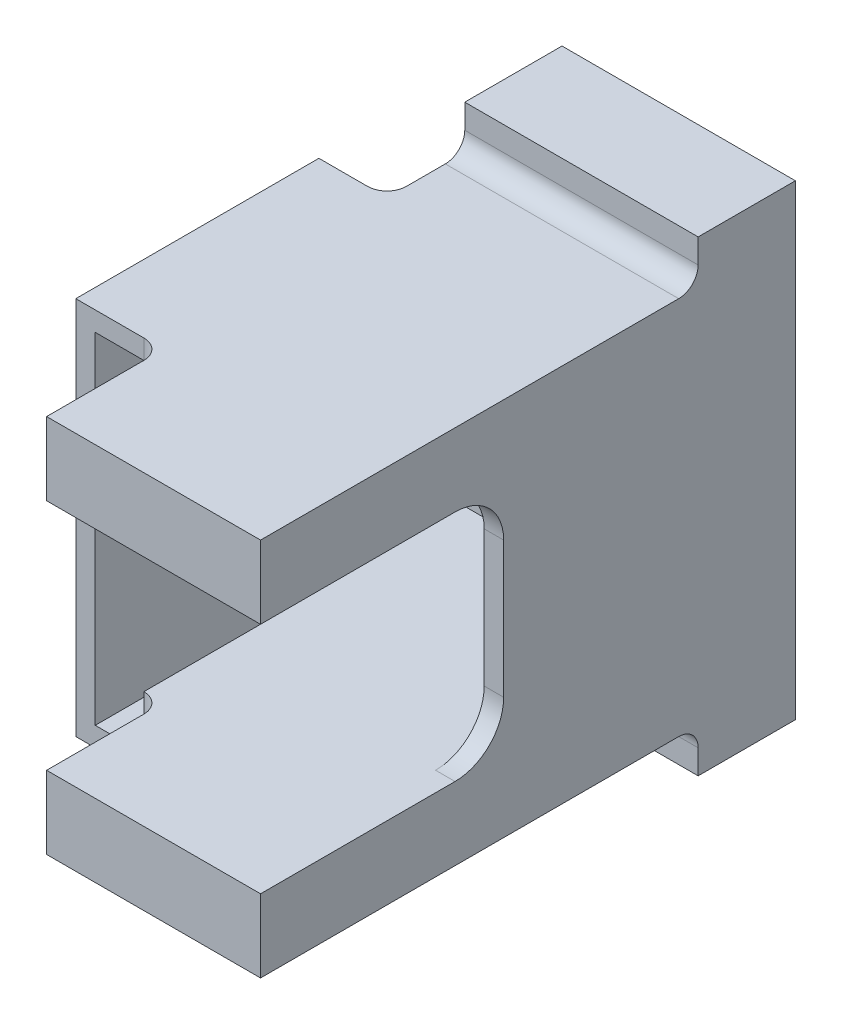
SolidWorks part; units mm, degrees
ref_plane "正面" through (0, 0, 0) normal (0, 0, 1) x (1, 0, 0)
ref_plane "平面" through (0, 0, 0) normal (0, 1, 0) x (1, 0, 0)
ref_plane "右側面" through (0, 0, 0) normal (1, 0, 0) x (0, 0, -1)
sketch "ｽｹｯﾁ2" plane through (0, 0, 0) normal (0, 0, 1) x (1, 0, 0)
  line L1 (-12, 14) -> (12, 14)
  line L2 (-12, 14) -> (-12, -14)
  line L3 (-12, -14) -> (12, -14)
  line L4 (12, 14) -> (12, -14)
  line L5 (-12, 14) -> (12, -14) construction
  line L6 (-12, -14) -> (12, 14) construction
  point P0 (0, 0)
  dimension "D1" = 24
  dimension "D2" = 28
extrude "ﾎﾞｽ - 押し出し1" add sketch "ｽｹｯﾁ2" along normal blind 22
sketch "ｽｹｯﾁ3" plane through (0, 0, 22) normal (0, 0, 1) x (1, 0, 0)
  line L1 (10, 12) -> (-10, 12)
  line L2 (10, 12) -> (10, -12)
  line L3 (10, -12) -> (-10, -12)
  line L4 (-10, 12) -> (-10, -12)
  line L5 (10, 12) -> (-10, -12) construction
  line L6 (10, -12) -> (-10, 12) construction
  point P0 (0, 0)
  dimension "D1" = 24
  dimension "D2" = 20
extrude "ｶｯﾄ - 押し出し1" cut sketch "ｽｹｯﾁ3" against normal blind 18
sketch "ｽｹｯﾁ4" plane through (0, 0, 4) normal (0, 0, 1) x (1, 0, 0)
  line L0 (10, -12) -> (10, 12) construction
  line L1 (-12, 6.5) -> (4, 6.5)
  line L2 (-12, 6.5) -> (-12, -6.5)
  line L3 (-12, -6.5) -> (4, -6.5)
  line L4 (4, 6.5) -> (4, -6.5)
  line L5 (-12, 6.5) -> (4, -6.5) construction
  line L6 (-12, -6.5) -> (4, 6.5) construction
  line L8 (-12, 14) -> (-12, -14) construction
  point P0 (-4, 0)
  dimension "D1" = 6
  dimension "D3" = 13
extrude "ｶｯﾄ - 押し出し3" cut sketch "ｽｹｯﾁ4" against normal through all
sketch "ｽｹｯﾁ6" plane through (-12, 0, 0) normal (-1, 0, 0) x (0, 0, 1)
  line L0 (22, 14) -> (22, -14) construction
  line L1 (22, 12) -> (2, 12)
  line L2 (22, 12) -> (22, -12)
  line L3 (22, -12) -> (2, -12)
  line L4 (2, 12) -> (2, -12)
  line L5 (22, 12) -> (2, -12) construction
  line L6 (22, -12) -> (2, 12) construction
  line L7 (22, 14) -> (0, 14) construction
  line L8 (22, -14) -> (0, -14) construction
  line L9 (0, 14) -> (0, 6.5) construction
  point P0 (12, 0)
  dimension "D1" = 2
  dimension "D2" = 2
  dimension "D3" = 2
extrude "ｶｯﾄ - 押し出し4" cut sketch "ｽｹｯﾁ6" against normal blind 5
sketch "ｽｹｯﾁ7" plane through (0, -14, 0) normal (0, -1, 0) x (1, 0, 0)
  line L0 (12, 22) -> (12, 0) construction
  line L1 (-12, 2) -> (12, 2)
  line L2 (-12, 2) -> (-12, 0)
  line L3 (-12, 0) -> (12, 0)
  line L4 (12, 2) -> (12, 0)
  line L5 (-12, 2) -> (12, 0) construction
  line L6 (-12, 0) -> (12, 2) construction
  point P0 (0, 1)
  dimension "D1" = 2
extrude "ﾎﾞｽ - 押し出し3" add sketch "ｽｹｯﾁ7" along normal blind 10
sketch "ｽｹｯﾁ8" plane through (0, 14, 0) normal (0, 1, 0) x (1, 0, 0)
  line L0 (12, 0) -> (-12, 0) construction
  line L1 (12, -2) -> (-12, -2)
  line L2 (12, -2) -> (12, 0)
  line L3 (12, 0) -> (-12, 0)
  line L4 (-12, -2) -> (-12, 0)
  line L5 (12, -2) -> (-12, 0) construction
  line L6 (12, 0) -> (-12, -2) construction
  line L7 (-12, -22) -> (-12, 0) construction
  line L8 (12, -22) -> (12, 0) construction
  point P0 (0, -1)
  dimension "D1" = 2
extrude "ﾎﾞｽ - 押し出し4" add sketch "ｽｹｯﾁ8" along normal blind 10
ref_plane "平面1" through (0, 0, 0) normal (1, 0, 0) x (0, 0, -1)
sketch "ｽｹｯﾁ9" plane through (0, 0, 0) normal (0, 0, -1) x (-1, 0, 0)
  line L0 (12, 17.5) -> (17, 17.5)
  line L2 (17, 17.5) -> (17, -17.5)
  line L3 (17, -17.5) -> (12, -17.5)
  line L5 (12, 24) -> (12, 6.5) construction
  line L7 (10, 19.5) -> (19, 19.5)
  line L8 (19, 19.5) -> (19, -19.5)
  line L9 (19, -19.5) -> (10, -19.5)
  line L12 (12, -6.5) -> (12, -24) construction
  line L13 (10, -19.5) -> (10, -12)
  line L14 (10, -12) -> (12, -12)
  line L15 (12, -12) -> (12, -17.5)
  line L16 (12, -6.5) -> (-4, -6.5) construction
  line L17 (10, 19.5) -> (10, 12)
  line L18 (10, 12) -> (12, 12)
  line L19 (12, 12) -> (12, 17.5)
  line L20 (-4, 6.5) -> (12, 6.5) construction
  point P2 (17, 0)
  dimension "D1" = 35
  dimension "D2" = 5
  dimension "D3" = 2
  dimension "D4" = 2
  dimension "D5" = 2
  dimension "D6" = 2
  dimension "D7" = 5.5
  dimension "D8" = 5.5
  dimension "D9" = 2
extrude "ﾎﾞｽ - 押し出し5" add sketch "ｽｹｯﾁ9" against normal blind 35
sketch "ｽｹｯﾁ10" plane through (0, 0, 22) normal (0, 0, 1) x (1, 0, 0)
  line L1 (-10, 12) -> (12, 12)
  line L2 (-10, 12) -> (-10, 14)
  line L3 (-10, 14) -> (12, 14)
  line L4 (12, 12) -> (12, 14)
  line L5 (-10, -12) -> (12, -12)
  line L6 (-10, -12) -> (-10, -14)
  line L7 (-10, -14) -> (12, -14)
  line L8 (12, -12) -> (12, -14)
extrude "ﾎﾞｽ - 押し出し6" add sketch "ｽｹｯﾁ10" along normal blind 25
fillet "ﾌｨﾚｯﾄ2" radius 5 2 edges at (11, 12, 22) (11, -12, 22)
sketch "ｽｹｯﾁ11" plane through (0, 19.5, 0) normal (0, 1, 0) x (1, 0, 0)
  line L0 (-19, -35) -> (-19, 0) construction
  line L1 (-12, 0) -> (-19, 0)
  line L2 (-12, 0) -> (-12, -10)
  line L3 (-12, -10) -> (-19, -10)
  line L4 (-19, 0) -> (-19, -10)
  dimension "D1" = 10
extrude "ｶｯﾄ - 押し出し5" cut sketch "ｽｹｯﾁ11" against normal through all
fillet "ﾌｨﾚｯﾄ4" radius 2 2 edges at (-12, -18.5, 10) (-12, 18.5, 10)
sketch "ｽｹｯﾁ12" plane through (0, 0, 0) normal (0, 0, -1) x (-1, 0, 0)
  line L0 (10, -8.5) -> (10, -22)
  line L1 (-12, 24) -> (12, 24)
  line L2 (-12, 24) -> (-12, 6.5)
  line L3 (-4, 6.5) -> (12, 6.5)
  line L4 (12, 24) -> (12, 6.5)
  line L5 (12, -6.5) -> (-4, -6.5)
  line L6 (12, -6.5) -> (12, -24)
  line L7 (12, -24) -> (-12, -24)
  line L8 (-12, -6.5) -> (-12, -24)
  line L9 (10, -22) -> (-10, -22)
  line L10 (-10, -8.5) -> (-10, -22)
  line L11 (10, -8.5) -> (-10, -8.5)
  line L12 (-10, 22) -> (10, 22)
  line L13 (10, 22) -> (10, 8.5)
  line L14 (-10, 8.5) -> (10, 8.5)
  line L15 (-10, 22) -> (-10, 8.5)
  line L16 (-12, 6.5) -> (-12, -6.5)
  line L17 (-4, 6.5) -> (-4, -6.5)
  line L18 (-4, -6.5) -> (-4, 6.5) construction
  line L19 (-12, 6.5) -> (12, 6.5) construction
  line L20 (-12, -24) -> (-12, 24) construction
  line L21 (12, -6.5) -> (-12, -6.5) construction
  point P26 (-12, 6.5)
  point P29 (-4.007, 6.5)
  dimension "D1" = 2
  dimension "D2" = 2
extrude "ﾎﾞｽ - 押し出し7" add sketch "ｽｹｯﾁ12" along normal blind 8
sketch "ｽｹｯﾁ13" plane through (0, 0, -8) normal (0, 0, -1) x (-1, 0, 0)
  line L0 (-10, 22) -> (10, 8.5)
  line L1 (10, 8.5) -> (10, 22) construction
  line L2 (-10, 8.5) -> (10, 8.5) construction
  line L3 (-10, 8.5) -> (10, 22)
  line L4 (-10, -8.5) -> (10, -22)
  line L5 (-10, -22) -> (10, -8.5)
rib "ﾘﾌﾞ1" sketch "ｽｹｯﾁ13" sketch "ｽｹｯﾁ13" thickness 2 extrusion direction normal to sketch draft on no parameters "D1"=2
sketch "ｽｹｯﾁ14" plane through (0, 0, 2) normal (0, 0, 1) x (1, 0, 0)
  line L0 (-10, 19.5) -> (-10, 14) construction
  line L1 (12, 14) -> (-10, 14)
  line L2 (12, 14) -> (12, 19.5)
  line L3 (12, 19.5) -> (-10, 19.5)
  line L4 (-10, 14) -> (-10, 19.5)
  line L5 (-10, 19.5) -> (-10, 14) construction
  line L7 (12, -14) -> (-10, -14)
  line L8 (12, -14) -> (12, -19.5)
  line L9 (12, -19.5) -> (-10, -19.5)
  line L10 (-10, -14) -> (-10, -19.5)
extrude "ﾎﾞｽ - 押し出し8" add sketch "ｽｹｯﾁ14" along normal blind 45
fillet "ﾌｨﾚｯﾄ5" radius 2 4 edges at (0, -19.5, 2) (0, 19.5, 2) (-10, -15.75, 35) (-10, 15.75, 35)
